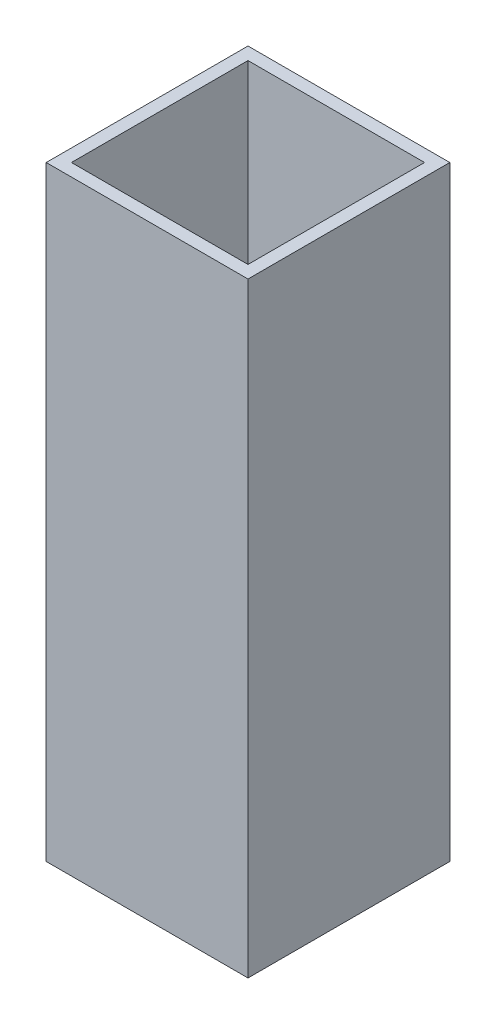
SolidWorks part; units mm, degrees
ref_plane "Front Plane" through (0, 0, 0) normal (0, 0, 1) x (1, 0, 0)
ref_plane "Top Plane" through (0, 0, 0) normal (0, 1, 0) x (1, 0, 0)
ref_plane "Right Plane" through (0, 0, 0) normal (1, 0, 0) x (0, 0, -1)
sketch "Sketch1" plane through (0, 0, 0) normal (0, 1, 0) x (1, 0, 0)
  line L1 (12.7, 12.7) -> (-12.7, 12.7)
  line L2 (12.7, 12.7) -> (12.7, -12.7)
  line L3 (12.7, -12.7) -> (-12.7, -12.7)
  line L4 (-12.7, 12.7) -> (-12.7, -12.7)
  line L5 (12.7, 12.7) -> (-12.7, -12.7) construction
  line L6 (12.7, -12.7) -> (-12.7, 12.7) construction
  line L7 (11.1125, 11.1125) -> (-11.1125, 11.1125)
  line L8 (11.1125, 11.1125) -> (11.1125, -11.1125)
  line L9 (11.1125, -11.1125) -> (-11.1125, -11.1125)
  line L10 (-11.1125, 11.1125) -> (-11.1125, -11.1125)
  line L11 (11.1125, 11.1125) -> (-11.1125, -11.1125) construction
  line L12 (11.1125, -11.1125) -> (-11.1125, 11.1125) construction
  point P1 (0, 0)
  point P6 (0, 0)
  dimension "D1" = 25.4
  dimension "D2" = 25.4
  dimension "D3" = 1.5875
  dimension "D4" = 1.5875
extrude "Boss-Extrude1" add sketch "Sketch1" along normal blind 76.2
